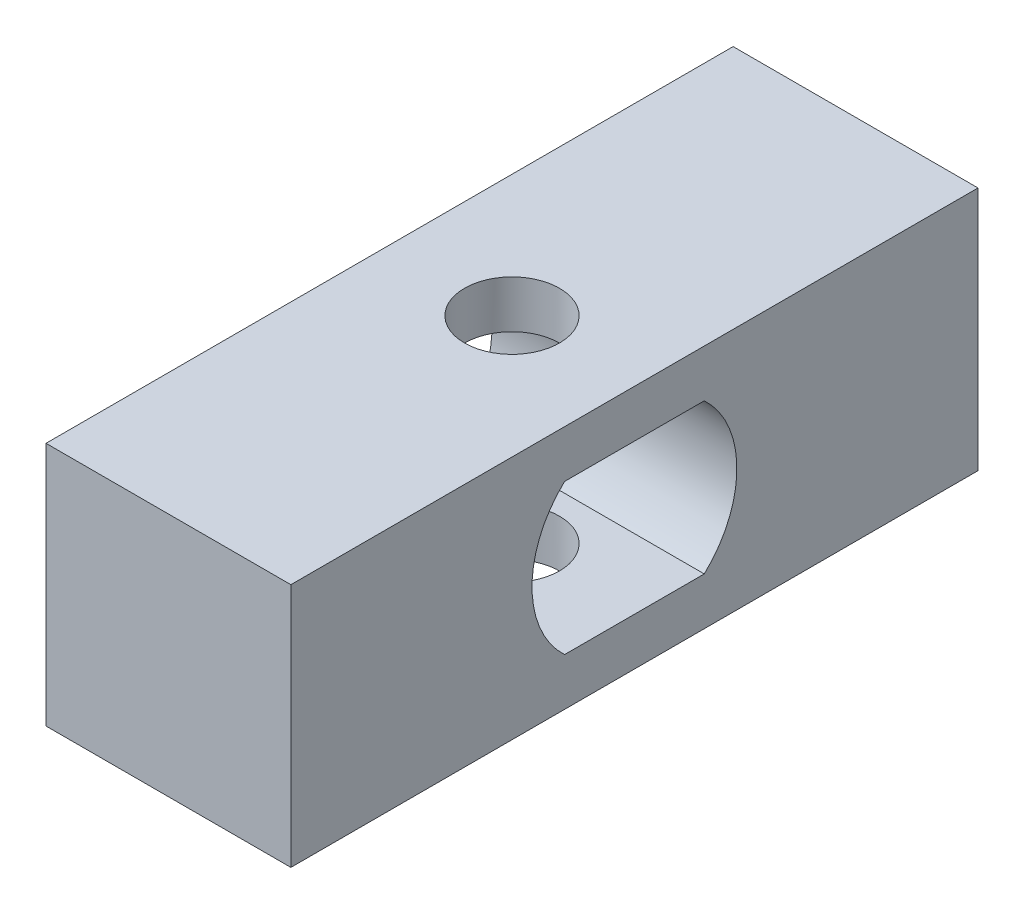
SolidWorks part; units mm, degrees
ref_plane "Front Plane" through (0, 0, 0) normal (0, 0, 1) x (1, 0, 0)
ref_plane "Top Plane" through (0, 0, 0) normal (0, 1, 0) x (1, 0, 0)
ref_plane "Right Plane" through (0, 0, 0) normal (1, 0, 0) x (0, 0, -1)
sketch "Sketch1" plane through (0, 0, 0) normal (0, 0, 1) x (1, 0, 0)
  line L1 (-6.223, -6.223) -> (6.223, -6.223)
  line L2 (-6.223, -6.223) -> (-6.223, 6.223)
  line L3 (-6.223, 6.223) -> (6.223, 6.223)
  line L4 (6.223, -6.223) -> (6.223, 6.223)
  line L5 (-6.223, -6.223) -> (6.223, 6.223) construction
  line L6 (-6.223, 6.223) -> (6.223, -6.223) construction
  point P0 (0, 0)
  dimension "D1" = 12.446
  dimension "D2" = 12.446
extrude "Boss-Extrude1" add sketch "Sketch1" along normal mid plane 34.925
sketch "Sketch2" plane through (6.223, 0, 0) normal (1, 0, 0) x (0, 0, -1)
  line L0 (0, 3.81) -> (0, 6.223) construction
  line L1 (-3.5492, -3.81) -> (3.5492, -3.81)
  line L2 (-3.5492, -3.81) -> (-3.5492, 3.81)
  line L3 (-3.5492, 3.81) -> (3.5492, 3.81)
  line L4 (3.5492, -3.81) -> (3.5492, 3.81)
  line L5 (-3.5492, -3.81) -> (3.5492, 3.81) construction
  line L6 (-3.5492, 3.81) -> (3.5492, -3.81) construction
  line L8 (0, -3.81) -> (0, -6.223) construction
  line L9 (-17.4625, -6.223) -> (17.4625, -6.223) construction
  circle A0 centre (0, 0) radius 5.207
  point P0 (0, 0)
  dimension "D2" = 10.414
  dimension "D1" = 7.62
extrude "Cut-Extrude1" cut sketch "Sketch2" against normal through all contours L2 A0 | L1 L4 L3 L2 | L4 A0
sketch "Sketch3" plane through (0, 6.223, 0) normal (0, 1, 0) x (1, 0, 0)
  circle A0 centre (0, 0) radius 2.413
  dimension "D1" = 4.826
extrude "Cut-Extrude2" cut sketch "Sketch3" against normal through all
